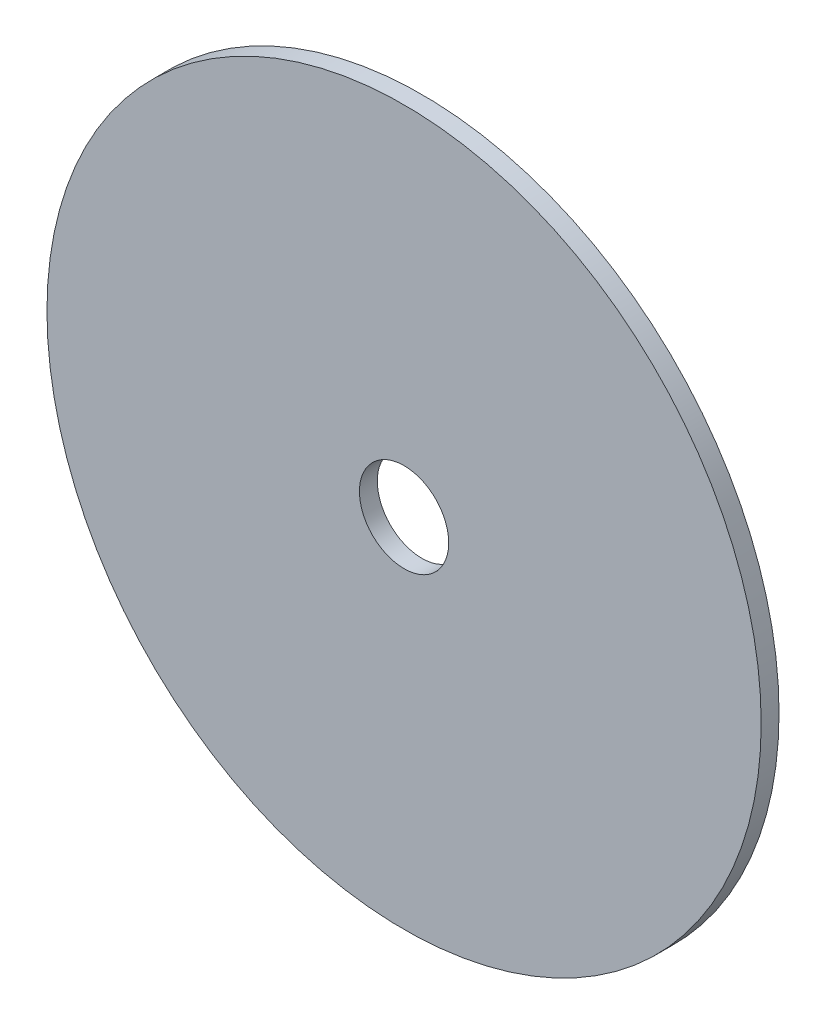
SolidWorks part; units mm, degrees
ref_plane "前视基准面" through (0, 0, 0) normal (0, 0, 1) x (1, 0, 0)
ref_plane "上视基准面" through (0, 0, 0) normal (0, 1, 0) x (1, 0, 0)
ref_plane "右视基准面" through (0, 0, 0) normal (1, 0, 0) x (0, 0, -1)
sketch "草图1" plane through (0, 0, 0) normal (0, 0, 1) x (1, 0, 0)
  circle A0 centre (0, 0) radius 40
  circle A1 centre (0, 0) radius 5
extrude "凸台-拉伸1" add sketch "草图1" along normal blind 2
